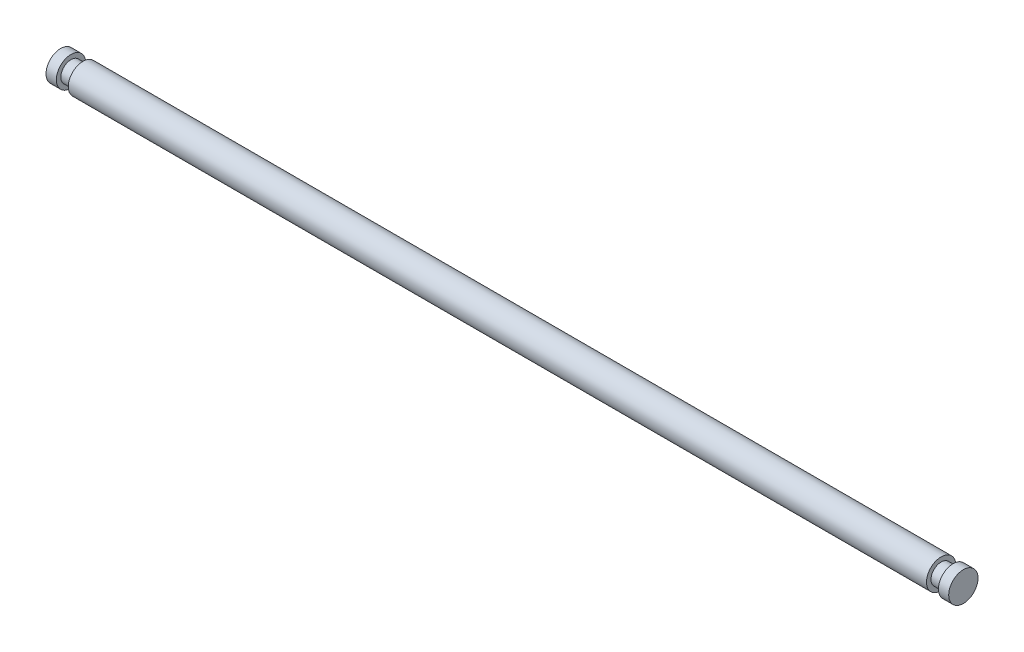
SolidWorks part; units mm, degrees
ref_plane "Front Plane" through (0, 0, 0) normal (1, 0, 0) x (0, 1, 0)
ref_plane "Top Plane" through (0, 0, 0) normal (0, 0, 1) x (0, 1, 0)
ref_plane "Right Plane" through (0, 0, 0) normal (0, 1, 0) x (-1, 0, 0)
sketch "Sketch1" plane through (0, 0, 0) normal (0, 0, 1) x (0, 1, 0)
  line L0 (0, 0) -> (31.7309, 0)
  line L1 (31.7309, 0) -> (31.7309, -22.352)
  line L2 (31.7309, -22.352) -> (22.0218, -22.352)
  line L3 (22.0218, -22.352) -> (22.0218, -48.1584)
  line L4 (22.0218, -48.1584) -> (31.7309, -48.1584)
  line L5 (31.7309, -48.1584) -> (31.7309, -1904.7206)
  line L6 (31.7309, -1904.7206) -> (22.0218, -1904.7206)
  line L7 (22.0218, -1904.7206) -> (22.0218, -1930.527)
  line L8 (22.0218, -1930.527) -> (31.7309, -1930.527)
  line L9 (31.7309, -1930.527) -> (31.7309, -1952.752)
  line L10 (31.7309, -1952.752) -> (0, -1952.752)
  line L11 (0, -1952.752) -> (0, 0)
  line L12 (0, 25.4) -> (0, -1978.152) construction
revolve "Revolve1" add sketch "Sketch1" angle 360 about L12
